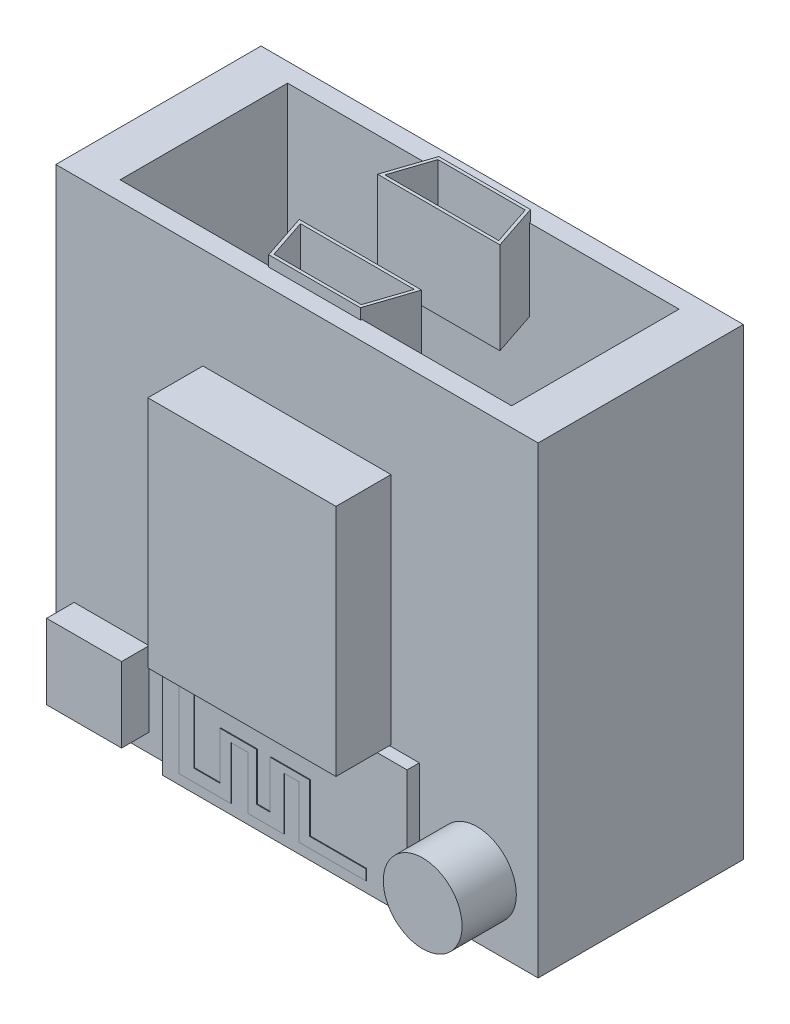
SolidWorks part; units mm, degrees
ref_plane "Plan de face" through (0, 0, 0) normal (0, 0, 1) x (1, 0, 0)
ref_plane "Plan de dessus" through (0, 0, 0) normal (0, 1, 0) x (1, 0, 0)
ref_plane "Plan de droite" through (0, 0, 0) normal (1, 0, 0) x (0, 0, -1)
sketch "Esquisse1" plane through (0, 0, 0) normal (0, 0, 1) x (1, 0, 0)
  line L1 (-15.77, 15.15) -> (15.77, 15.15)
  line L2 (-15.77, 15.15) -> (-15.77, -15.15)
  line L3 (-15.77, -15.15) -> (15.77, -15.15)
  line L4 (15.77, 15.15) -> (15.77, -15.15)
  line L5 (-15.77, 15.15) -> (15.77, -15.15) construction
  line L6 (-15.77, -15.15) -> (15.77, 15.15) construction
  point P0 (0, 0)
  dimension "D1" = 31.54
  dimension "D2" = 30.3
extrude "Boss.-Extru.1" add sketch "Esquisse1" along normal mid plane 13.42
sketch "Esquisse2" plane through (0, 0, 6.71) normal (0, 0, 1) x (1, 0, 0)
  line L0 (0, 15.15) -> (0, -15.15) construction
  line L1 (-6.15, 8.55) -> (6.15, 8.55)
  line L2 (-6.15, 8.55) -> (-6.15, -6.75)
  line L3 (-6.15, -6.75) -> (6.15, -6.75)
  line L4 (6.15, 8.55) -> (6.15, -6.75)
  line L5 (15.77, 15.15) -> (-15.77, 15.15) construction
  line L6 (-15.77, -15.15) -> (15.77, -15.15) construction
  dimension "D1" = 12.3
  dimension "D2" = 15.3
  dimension "D3" = 6.6
extrude "Boss.-Extru.2" add sketch "Esquisse2" along normal blind 3.6
sketch "Esquisse9" plane through (0, 15.15, 0) normal (0, 1, 0) x (1, 0, 0)
  line L0 (-15.77, 0) -> (15.77, 0) construction
  line L1 (-15.77, -6.71) -> (-15.77, 6.71) construction
  line L2 (15.77, -6.71) -> (15.77, 6.71) construction
  line L3 (0, 6.71) -> (0, -6.71) construction
  line L4 (15.77, 6.71) -> (-15.77, 6.71) construction
  line L5 (15.77, -6.71) -> (-15.77, -6.71) construction
  line L7 (-12.8, 5.475) -> (12.8, 5.475)
  line L8 (-12.8, 5.475) -> (-12.8, -5.475)
  line L9 (-12.8, -5.475) -> (12.8, -5.475)
  line L10 (12.8, 5.475) -> (12.8, -5.475)
  dimension "D1" = 25.6
  dimension "D2" = 10.95
extrude "Enlèv. mat.-Extru.2" cut sketch "Esquisse9" against normal through all
sketch "Esquisse3" plane through (0, 15.15, 0) normal (0, 1, 0) x (1, 0, 0)
  line L0 (0, 6.71) -> (0, -6.71) construction
  line L1 (15.77, 6.71) -> (-15.77, 6.71) construction
  line L2 (15.77, -6.71) -> (-15.77, -6.71) construction
  line L3 (-4, -2.56) -> (-3, -5.56)
  line L4 (-4, -2.56) -> (4, -2.56)
  line L5 (4, -2.56) -> (3, -5.56)
  line L6 (-3, -5.56) -> (3, -5.56)
  point P8 (0, -5.41)
  point P12 (0, -2.56)
  dimension "D1" = 8
  dimension "D2" = 3
  dimension "D3" = 1.15
  dimension "D4" = 6
extrude "Boss.-Extru.3" add sketch "Esquisse3" along normal blind 0.7 and the other way blind 5.3
sketch "Esquisse4" plane through (0, 15.85, 0) normal (0, 1, 0) x (1, 0, 0)
  line L8 (3.7225, -2.76) -> (-3.7225, -2.76)
  line L9 (-3.7225, -2.76) -> (-2.8558, -5.36)
  line L10 (-2.8558, -5.36) -> (2.8558, -5.36)
  line L11 (2.8558, -5.36) -> (3.7225, -2.76)
  line L12 (3.7225, -2.76) -> (-3.7225, -2.76)
  line L13 (-3.7225, -2.76) -> (-2.8558, -5.36)
  line L14 (-2.8558, -5.36) -> (2.8558, -5.36)
  line L15 (2.8558, -5.36) -> (3.7225, -2.76)
  dimension "D1" = 0.2
extrude "Enlèv. mat.-Extru.1" cut sketch "Esquisse4" against normal blind 3.4
mirror "Symétrie1" about plane through (0, 0, 0) normal (0, 0, 1) of "Boss.-Extru.3", "Enlèv. mat.-Extru.1"
sketch "Esquisse5" plane through (0, 0, 6.71) normal (0, 0, 1) x (1, 0, 0)
  line L1 (0, -15.15) -> (0, 15.15) construction
  line L2 (-15.77, -15.15) -> (15.77, -15.15) construction
  line L3 (15.77, 15.15) -> (-15.77, 15.15) construction
  line L6 (-8, -6.85) -> (8, -6.85)
  line L7 (-8, -6.85) -> (-8, -15.15)
  line L8 (-8, -15.15) -> (8, -15.15)
  line L9 (8, -6.85) -> (8, -15.15)
  dimension "D1" = 16
  dimension "D2" = 8.3
extrude "Boss.-Extru.4" add sketch "Esquisse5" along normal blind 0.8
sketch "Esquisse6" plane through (0, 0, 7.51) normal (0, 0, 1) x (1, 0, 0)
  line L1 (-6.8658, -7.5485) -> (-5.892, -7.5485)
  line L2 (-6.8658, -7.5485) -> (-6.8658, -14.4709)
  line L3 (-6.8658, -14.4709) -> (-5.892, -14.4709)
  line L4 (-5.892, -7.5485) -> (-5.892, -13.6722)
  line L5 (-5.892, -14.4709) -> (-3.4689, -14.4709)
  line L7 (-5.892, -13.6722) -> (-4.1913, -13.6722)
  line L8 (-3.4689, -14.4709) -> (-3.4689, -13.6722)
  line L10 (-3.4689, -13.6722) -> (-3.4689, -11.0097)
  line L12 (-4.1913, -13.6722) -> (-4.1913, -11.0097)
  line L13 (-3.4689, -11.0097) -> (-2.368, -11.0097)
  line L14 (-4.1913, -11.0097) -> (-4.1913, -10.5598)
  line L15 (-4.1913, -10.5598) -> (-1.7955, -10.5598)
  line L16 (-1.7955, -11.0097) -> (-1.7955, -10.5598)
  line L18 (-1.7955, -11.0097) -> (-1.7955, -13.6722)
  line L19 (-1.7955, -14.4709) -> (-2.368, -14.4709)
  line L20 (-2.368, -11.0097) -> (-2.368, -14.4709)
  line L21 (-1.7955, -14.4709) -> (0, -14.4709)
  line L23 (-1.7955, -13.6722) -> (-0.8978, -13.6722)
  line L24 (0, -14.4709) -> (0, -13.6722)
  line L26 (0, -13.6722) -> (0, -11.0097)
  line L27 (0, -10.5598) -> (-0.8978, -10.5598)
  line L28 (-0.8978, -13.6722) -> (-0.8978, -10.5598)
  line L29 (0, -10.5598) -> (1.6768, -10.5598)
  line L31 (0, -11.0097) -> (0.9897, -11.0097)
  line L32 (1.6768, -10.5598) -> (1.6768, -11.0097)
  line L34 (1.6768, -11.0097) -> (1.6768, -13.7512)
  line L35 (1.6768, -14.4335) -> (0.9897, -14.4335)
  line L36 (0.9897, -11.0097) -> (0.9897, -14.4335)
  line L37 (1.6768, -14.4335) -> (5.3611, -14.4335)
  line L39 (1.6768, -13.7512) -> (5.3611, -13.7512)
  line L40 (5.3611, -14.4335) -> (5.3611, -13.7512)
extrude "Boss.-Extru.5" add sketch "Esquisse6" along normal blind 0.05
sketch "Esquisse7" plane through (0, 0, 6.71) normal (0, 0, 1) x (1, 0, 0)
  line L0 (-15.77, 15.15) -> (-15.77, -15.15) construction
  line L1 (-14.57, -9.05) -> (-9.67, -9.05)
  line L2 (-14.57, -9.05) -> (-14.57, -13.95)
  line L3 (-14.57, -13.95) -> (-9.67, -13.95)
  line L4 (-9.67, -9.05) -> (-9.67, -13.95)
  line L5 (-15.77, -15.15) -> (-8, -15.15) construction
  dimension "D1" = 4.9
  dimension "D2" = 4.9
  dimension "D3" = 1.2
  dimension "D4" = 1.2
extrude "Boss.-Extru.6" add sketch "Esquisse7" along normal blind 1.8
sketch "Esquisse8" plane through (0, 0, 6.71) normal (0, 0, 1) x (1, 0, 0)
  line L0 (15.77, -15.15) -> (15.77, 15.15) construction
  line L1 (8, -15.15) -> (15.77, -15.15) construction
  circle A0 centre (11.77, -11.15) radius 2.575
  dimension "D1" = 5.15
  dimension "D2" = 4
  dimension "D3" = 4
extrude "Boss.-Extru.7" add sketch "Esquisse8" along normal blind 3.55
sketch "Esquisse10" plane through (0, -15.15, 0) normal (0, -1, 0) x (1, 0, 0)
  line L0 (0, 5.475) -> (0, -6.71) construction
  line L1 (-12.8, 5.475) -> (12.8, 5.475) construction
  line L2 (-15.77, -6.71) -> (15.77, -6.71) construction
  line L3 (-15.77, 6.71) -> (-8, 6.71) construction
  line L4 (-3.5, 5.51) -> (3.5, 5.51)
  line L5 (-3.5, 5.51) -> (-3.5, 2.21)
  line L6 (-3.5, 2.21) -> (3.5, 2.21)
  line L7 (3.5, 5.51) -> (3.5, 2.21)
  line L8 (-9.975, -2.21) -> (-2.975, -2.21)
  line L9 (-9.975, -2.21) -> (-9.975, -5.51)
  line L10 (-9.975, -5.51) -> (-2.975, -5.51)
  line L11 (-2.975, -2.21) -> (-2.975, -5.51)
  line L12 (2.975, -2.21) -> (2.975, -5.51)
  line L13 (9.975, -5.51) -> (2.975, -5.51)
  line L14 (9.975, -2.21) -> (9.975, -5.51)
  line L15 (9.975, -2.21) -> (2.975, -2.21)
  dimension "D1" = 3.3
  dimension "D2" = 4.5
  dimension "D3" = 7
  dimension "D4" = 4.5
  dimension "D5" = 3.3
  dimension "D6" = 19.95
  dimension "D7" = 7
extrude "Boss.-Extru.8" add sketch "Esquisse10" against normal blind 2.45
sketch "Esquisse11" plane through (0, -15.15, 0) normal (0, -1, 0) x (1, 0, 0)
  line L0 (-6.475, -2.21) -> (-6.475, -5.8695) construction
  line L1 (-2.975, -2.21) -> (-9.975, -2.21) construction
  line L2 (0, 2.21) -> (0, 5.9077) construction
  line L3 (-3.5, 2.21) -> (3.5, 2.21) construction
  line L4 (-3.5, 3.8425) -> (3.5, 3.8425) construction
  line L5 (-1.5, 4.5825) -> (1.5, 4.5825)
  line L6 (-1.5, 4.5825) -> (-1.5, 3.1025)
  line L7 (-1.5, 3.1025) -> (1.5, 3.1025)
  line L8 (1.5, 4.5825) -> (1.5, 3.1025)
  line L9 (-7.975, -3.1025) -> (-4.975, -3.1025)
  line L10 (-7.975, -3.1025) -> (-7.975, -4.5825)
  line L11 (-7.975, -4.5825) -> (-4.975, -4.5825)
  line L12 (-4.975, -3.1025) -> (-4.975, -4.5825)
  line L13 (-3.5, 5.475) -> (-3.5, 2.21) construction
  line L14 (3.5, 2.21) -> (3.5, 5.475) construction
  line L15 (-9.975, -3.8425) -> (-2.975, -3.8425) construction
  line L16 (-9.975, -2.21) -> (-9.975, -5.475) construction
  line L17 (-2.975, -5.475) -> (-2.975, -2.21) construction
  line L18 (4.975, -3.1025) -> (4.975, -4.5825)
  line L19 (7.975, -4.5825) -> (4.975, -4.5825)
  line L20 (7.975, -3.1025) -> (7.975, -4.5825)
  line L21 (7.975, -3.1025) -> (4.975, -3.1025)
  dimension "D1" = 3
  dimension "D2" = 1.48
  dimension "D3" = 1.48
  dimension "D4" = 3
extrude "Boss.-Extru.9" add sketch "Esquisse11" along normal blind 0.3
